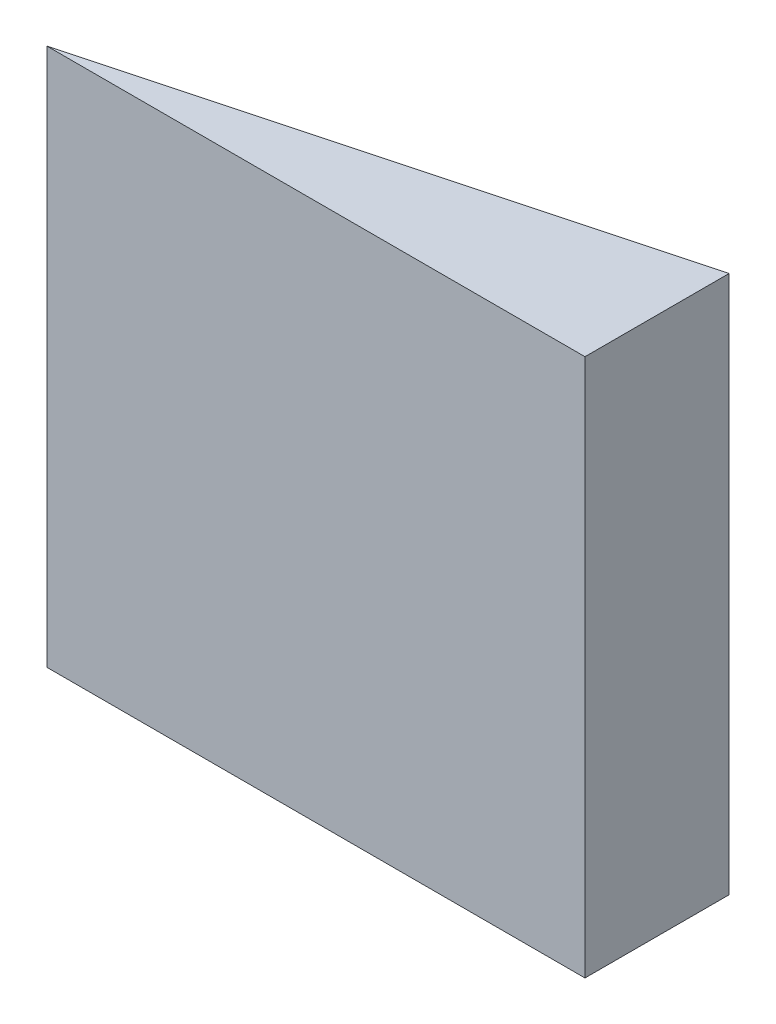
SolidWorks part; units mm, degrees
ref_plane "Front" through (0, 0, 0) normal (0, 0, 1) x (1, 0, 0)
ref_plane "Top" through (0, 0, 0) normal (0, 1, 0) x (1, 0, 0)
ref_plane "Right" through (0, 0, 0) normal (1, 0, 0) x (0, 0, -1)
sketch "Sketch1" plane through (0, 0, 0) normal (0, 1, 0) x (1, 0, 0)
  line L0 (48.006, 12.8632) -> (0, 0)
  line L1 (0, 0) -> (48.006, 0)
  line L2 (0, 0) -> (0, 12.8632)
  line L3 (0, 12.8632) -> (48.006, 12.8632)
  line L4 (48.006, 0) -> (48.006, 12.8632)
  dimension "D1" = 48.006
extrude "Boss-Extrude1" add sketch "Sketch1" along normal blind 48 contours L1 L4 L0
